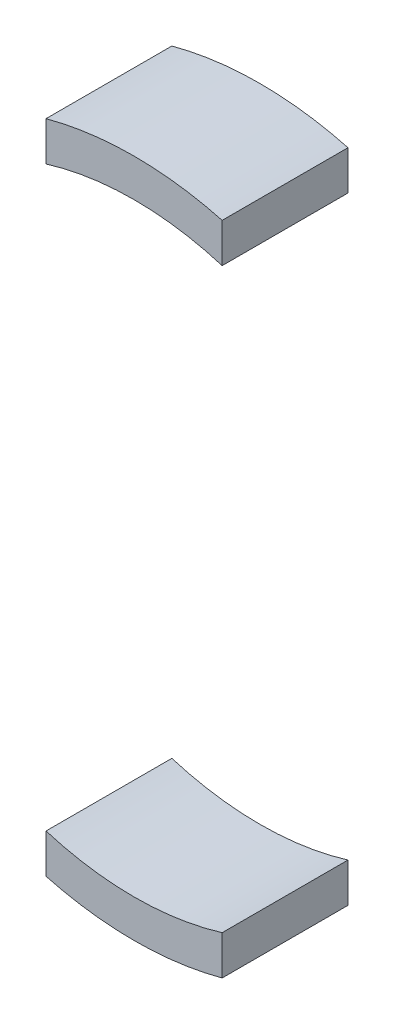
SolidWorks part; units mm, degrees
material "Alliage de zinc AC41A, brut"
ref_plane "Plan de face" through (0, 0, 0) normal (0, 0, 1) x (1, 0, 0)
ref_plane "Plan de dessus" through (0, 0, 0) normal (0, 1, 0) x (1, 0, 0)
ref_plane "Plan de droite" through (0, 0, 0) normal (1, 0, 0) x (0, 0, -1)
sketch "Esquisse1" plane through (0, 0, 0) normal (0, 0, 1) x (1, 0, 0)
  line L0 (0, -6.75) -> (0, 6.75) construction
  line L1 (1.75, 6.5192) -> (1.75, 5.7391)
  line L2 (-1.75, 6.5192) -> (-1.75, 5.7391)
  line L3 (-1.75, -5.7391) -> (-1.75, -6.5192)
  line L4 (1.75, -5.7391) -> (1.75, -6.5192)
  arc A0 (1.75, 6.5192) -> (-1.75, 6.5192) centre (0, 0) ccw
  arc A1 (1.75, 5.7391) -> (-1.75, 5.7391) centre (0, 0) ccw
  arc A2 (-1.75, -6.5192) -> (1.75, -6.5192) centre (0, 0) ccw
  arc A3 (-1.75, -5.7391) -> (1.75, -5.7391) centre (0, 0) ccw
  dimension "D1" = 13.5
  dimension "D2" = 12
  dimension "D3" = 1.75
  dimension "D4" = 1.75
extrude "Boss.-Extru.1" add sketch "Esquisse1" along normal blind 2.5
